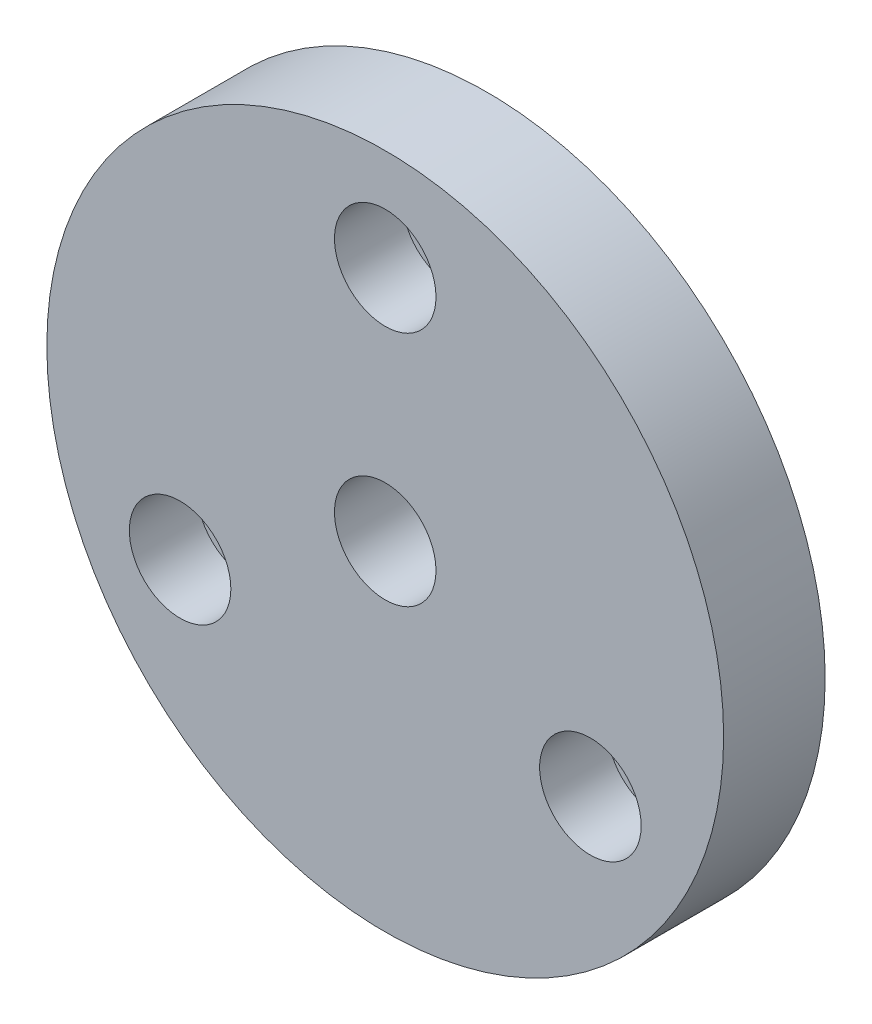
SolidWorks part; units mm, degrees
ref_plane "Plan de face" through (0, 0, 0) normal (0, 0, 1) x (1, 0, 0)
ref_plane "Plan de dessus" through (0, 0, 0) normal (0, 1, 0) x (1, 0, 0)
ref_plane "Plan de droite" through (0, 0, 0) normal (1, 0, 0) x (0, 0, -1)
sketch "Esquisse1" plane through (0, 0, 0) normal (0, 0, 1) x (1, 0, 0)
  circle A0 centre (0, 0) radius 20
  circle A1 centre (0, 0) radius 3
  dimension "D1" = 40
  dimension "D2" = 6
extrude "Extrusion1" add sketch "Esquisse1" along normal blind 6
sketch "Esquisse2" plane through (0, 0, 6) normal (0, 0, 1) x (1, 0, 0)
  circle A0 centre (0, 14) radius 3
  circle A1 centre (12.1244, -7) radius 3
  circle A2 centre (-12.1244, -7) radius 3
  dimension "D1" = 6
  dimension "D2" = 14
extrude "Enlèv. mat.-Extru.1" cut sketch "Esquisse2" against normal blind 4
